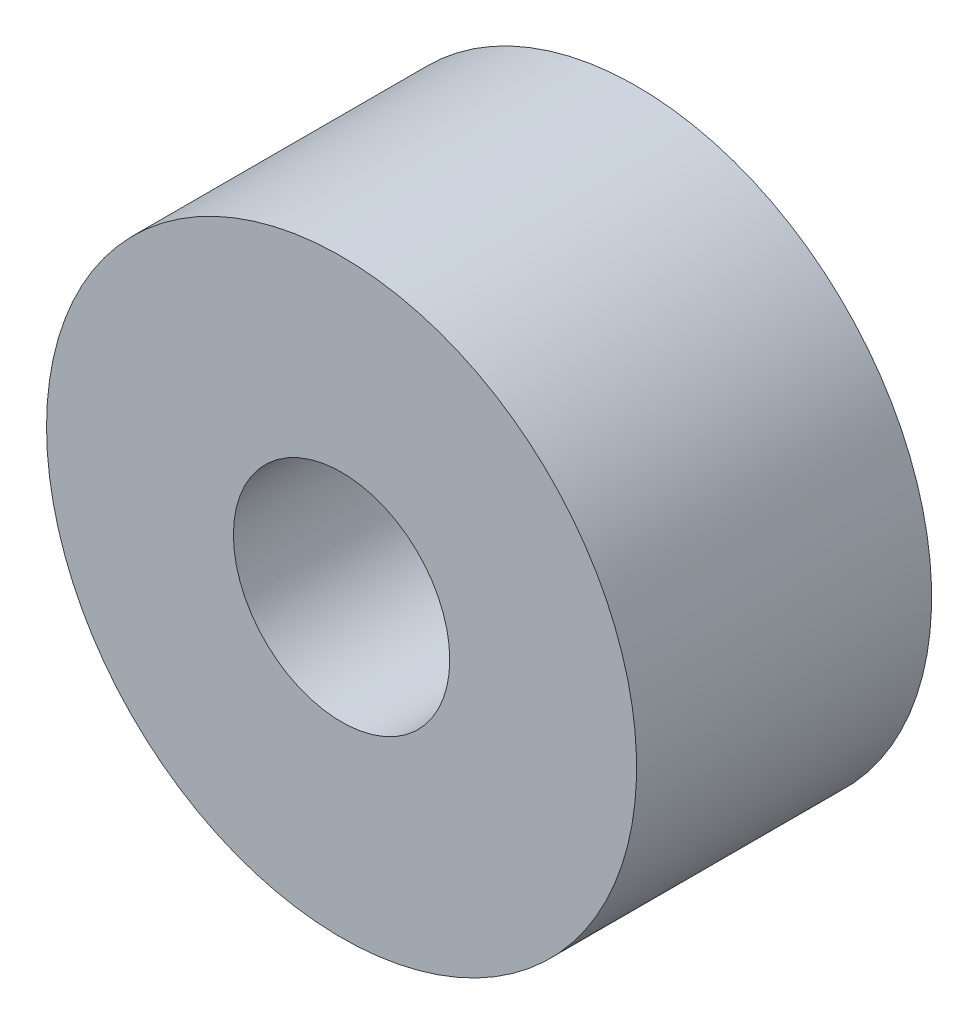
SolidWorks part; units mm, degrees
material "Plain Carbon Steel"
ref_plane "Front Plane" through (0, 0, 0) normal (0, 0, 1) x (1, 0, 0)
ref_plane "Top Plane" through (0, 0, 0) normal (0, 1, 0) x (1, 0, 0)
ref_plane "Right Plane" through (0, 0, 0) normal (1, 0, 0) x (0, 0, -1)
sketch "Sketch2" plane through (0, 0, 0) normal (0, 0, 1) x (1, 0, 0)
  circle A0 centre (-14.4046, 1.0568) radius 9.525
  dimension "D1" = 19.05
extrude "Boss-Extrude1" add sketch "Sketch2" along normal blind 9.525 contours A0
sketch "Sketch4" plane through (0, 0, 0) normal (0, 0, -1) x (-1, 0, 0)
  circle A0 centre (14.4046, 1.0568) radius 4.7625
  dimension "D1" = 9.525
extrude "Boss-Extrude2" add sketch "Sketch4" along normal blind 3.175
sketch "Sketch8" plane through (0, 0, -3.175) normal (0, 0, -1) x (-1, 0, 0)
  line L0 (9.6421, 1.0568) -> (10.9121, 1.0568)
  circle A0 centre (14.4046, 1.0568) radius 3.4925
  circle A1 centre (14.4046, 1.0568) radius 4.7625 construction
  circle A2 centre (14.4046, 1.0568) radius 4.7625 construction
  dimension "D1" = 1.27
extrude "Cut-Extrude1" cut sketch "Sketch8" against normal through all contours A0
